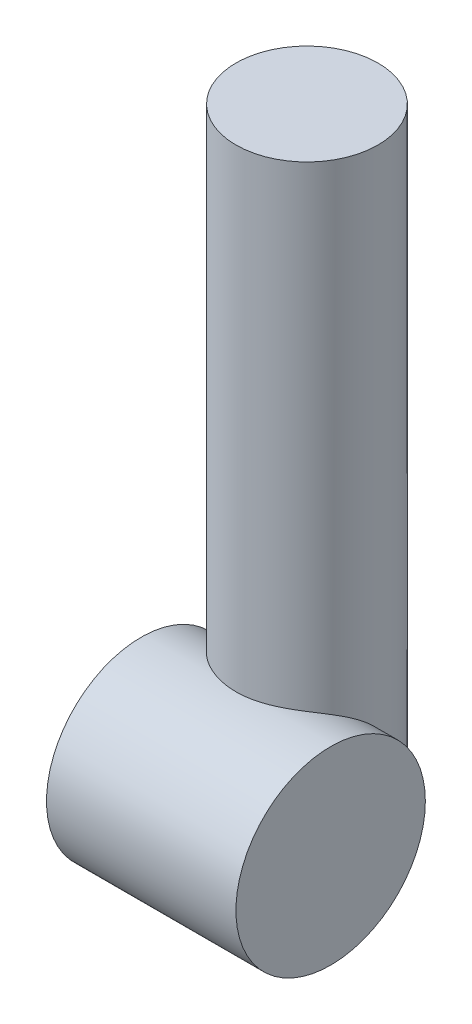
SolidWorks part; units mm, degrees
ref_plane "前视基准面" through (0, 0, 0) normal (0, 0, 1) x (1, 0, 0)
ref_plane "上视基准面" through (0, 0, 0) normal (0, 1, 0) x (1, 0, 0)
ref_plane "右视基准面" through (0, 0, 0) normal (1, 0, 0) x (0, 0, -1)
sketch "草图1" plane through (0, 0, 0) normal (0, 1, 0) x (1, 0, 0)
  circle A0 centre (0, 0) radius 30
  dimension "D1" = 60
extrude "凸台-拉伸1" add sketch "草图1" along normal blind 240
sketch "草图2" plane through (0, 0, 0) normal (1, 0, 0) x (0, 0, -1)
  circle A0 centre (-30, 0) radius 40
  point P2 (0, 0)
  dimension "D2" = 80
  dimension "D1" = 30
extrude "凸台-拉伸2" add sketch "草图2" along normal mid plane 80
